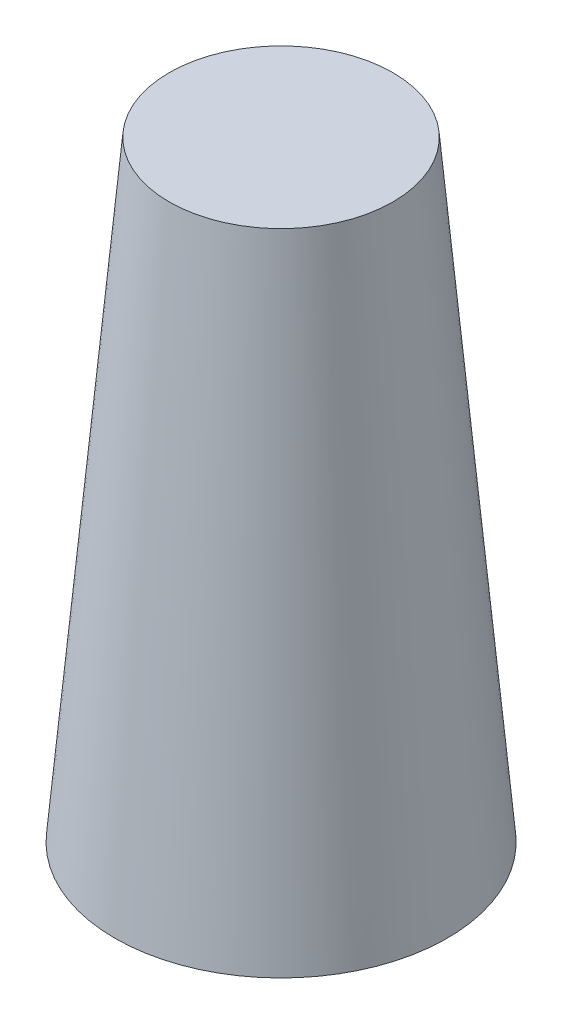
SolidWorks part; units mm, degrees
material "ABS"
ref_plane "Front Plane" through (0, 0, 0) normal (0, 0, 1) x (1, 0, 0)
ref_plane "Top Plane" through (0, 0, 0) normal (0, 1, 0) x (1, 0, 0)
ref_plane "Right Plane" through (0, 0, 0) normal (1, 0, 0) x (0, 0, -1)
sketch "Sketch1" plane through (0, 0, 0) normal (0, 1, 0) x (1, 0, 0)
  circle A0 centre (0, 0) radius 6.223
  dimension "D1" = 12.446
ref_plane "Plane1" through (0, 22.86, 0) normal (0, 1, 0) x (1, 0, 0)
sketch "Sketch2" plane through (0, 22.86, 0) normal (0, 1, 0) x (1, 0, 0)
  circle A0 centre (0, 0) radius 4.191
  dimension "D1" = 8.382
loft "Loft1" add profiles "Sketch2", "Sketch1"
